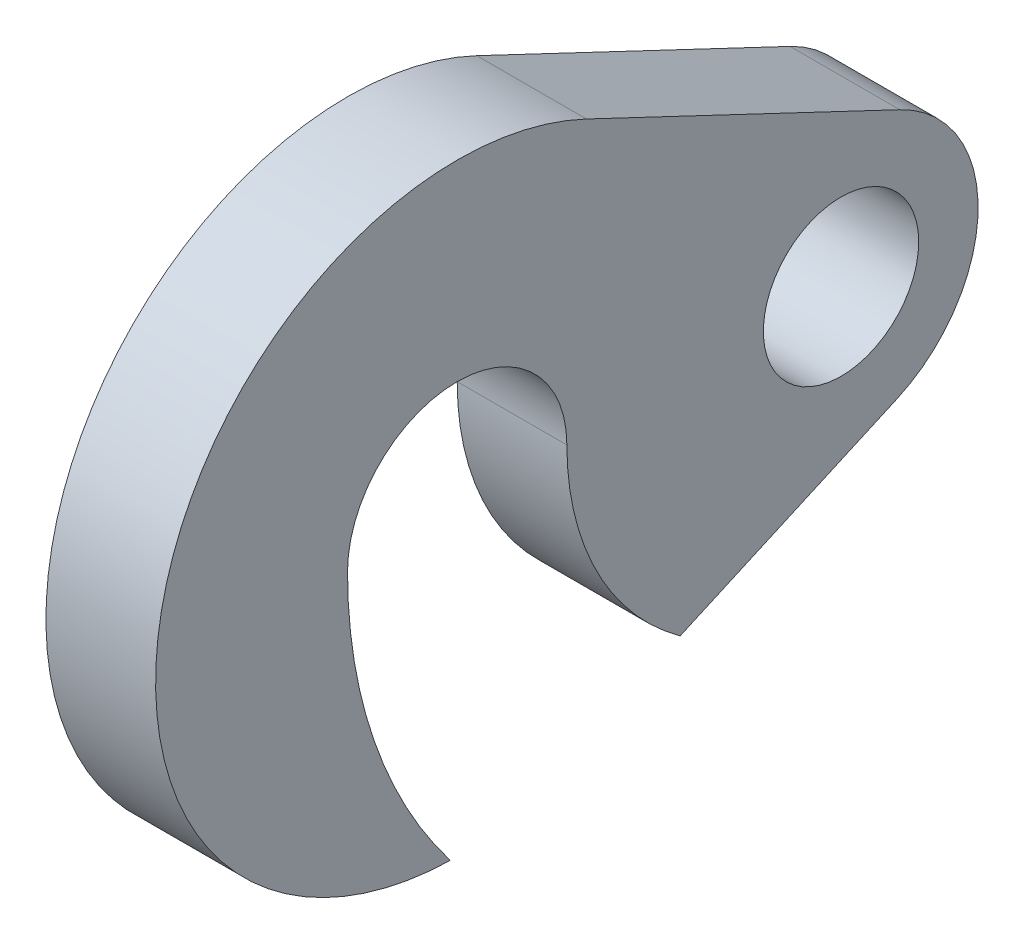
SolidWorks part; units mm, degrees
material "AISI 304"
ref_plane "Front Plane" through (0, 0, 0) normal (0, 0, 1) x (1, 0, 0)
ref_plane "Top Plane" through (0, 0, 0) normal (0, 1, 0) x (1, 0, 0)
ref_plane "Right Plane" through (0, 0, 0) normal (1, 0, 0) x (0, 0, -1)
sketch "Sketch1" plane through (0, 0, 0) normal (1, 0, 0) x (0, 0, -1)
  line L0 (0, 78.0032) -> (0, -91.1795) construction
  line L1 (-66.9272, 0) -> (62.457, 0) construction
  line L2 (-42, 60.5624) -> (-42, -38.5241) construction
  line L3 (-17.601, -24.2941) -> (6.1194, -13.695)
  line L4 (-27.8571, 29.8158) -> (6.4286, 13.5526)
  circle A0 centre (0, 0) radius 8.5
  arc A1 (-54, 0) -> (-30, 0) centre (-42, 0) cw
  arc A2 (-30, 0) -> (-17.601, -24.2941) centre (0, 0) ccw
  arc A3 (6.4286, 13.5526) -> (6.1194, -13.695) centre (0, 0) cw
  arc A4 (-27.8571, 29.8158) -> (-42.75, -32.9915) centre (-42, 0) ccw
  arc A5 (-54, 0) -> (-42.75, -32.9915) centre (0, 0) ccw
  dimension "D2" = 17
  dimension "D4" = 12
  dimension "D6" = 15
  dimension "D7" = 33
  dimension "D1" = 42
extrude "Boss-Extrude1" add sketch "Sketch1" along normal blind 12
